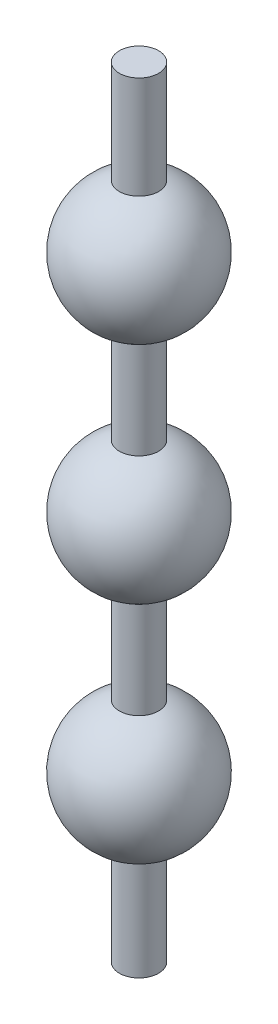
SolidWorks part; units mm, degrees
ref_plane "Front Plane" through (0, 0, 0) normal (0, 0, 1) x (1, 0, 0)
ref_plane "Top Plane" through (0, 0, 0) normal (0, 1, 0) x (1, 0, 0)
ref_plane "Right Plane" through (0, 0, 0) normal (1, 0, 0) x (0, 0, -1)
sketch "Sketch1" plane through (0, 0, 0) normal (0, 1, 0) x (1, 0, 0)
  circle A0 centre (0, 0) radius 1.905
  dimension "D1" = 3.81
extrude "Boss-Extrude1" add sketch "Sketch1" along normal blind 10.16
sketch "Sketch3" plane through (0, 0, 0) normal (0, 0, 1) x (1, 0, 0)
  line L0 (0, 9.652) -> (0, 22.352)
  line L2 (1.905, 10.16) -> (-1.905, 10.16) construction
  arc A0 (0, 9.652) -> (0, 22.352) centre (0, 16.002) ccw
  point P2 (0, 9.3041)
  dimension "D1" = 12.7
  dimension "D2" = 0.508
revolve "Revolve1" add sketch "Sketch3" angle 360 about L0
ref_plane "Plane1" through (0, 21.844, 0) normal (0, -1, 0) x (-1, 0, 0)
sketch "Sketch4" plane through (0, 21.844, 0) normal (0, -1, 0) x (-1, 0, 0)
  circle A0 centre (0, 0) radius 1.905
  dimension "D1" = 3.81
extrude "Boss-Extrude2" add sketch "Sketch4" against normal blind 10.16 contours A0
sketch "Sketch6" plane through (0, 0, 0) normal (0, 0, 1) x (1, 0, 0)
  line L0 (0, 31.496) -> (0, 44.196)
  line L1 (1.905, 32.004) -> (-1.905, 32.004) construction
  arc A0 (0, 31.496) -> (0, 44.196) centre (0, 37.846) ccw
  dimension "D1" = 12.7
  dimension "D2" = 0.508
revolve "Revolve2" add sketch "Sketch6" angle 360 about L0
ref_plane "Plane2" through (0, 43.688, 0) normal (0, -1, 0) x (-1, 0, 0)
sketch "Sketch7" plane through (0, 43.688, 0) normal (0, -1, 0) x (-1, 0, 0)
  circle A0 centre (0, 0) radius 1.905
  dimension "D1" = 3.81
extrude "Boss-Extrude3" add sketch "Sketch7" against normal blind 10.16
sketch "Sketch8" plane through (0, 0, 0) normal (1, 0, 0) x (0, 0, -1)
  line L0 (0, 53.34) -> (0, 66.04)
  line L1 (1.905, 53.848) -> (-1.905, 53.848) construction
  arc A0 (0, 53.34) -> (0, 66.04) centre (0, 59.69) ccw
  dimension "D1" = 12.7
  dimension "D2" = 0.508
revolve "Revolve3" add sketch "Sketch8" angle 360 about L0
ref_plane "Plane3" through (0, 65.532, 0) normal (0, -1, 0) x (-1, 0, 0)
sketch "Sketch9" plane through (0, 65.532, 0) normal (0, -1, 0) x (-1, 0, 0)
  circle A0 centre (0, 0) radius 1.905
  dimension "D1" = 3.81
extrude "Boss-Extrude4" add sketch "Sketch9" against normal blind 10.16
equation "\"Connector Diameter\"= .15"
equation "\"Ball Diameter\"= .5"
equation "\"Connector Length\"= .4"
equation "\"D1@Sketch1\"=\"Connector Diameter\""
equation "\"D1@Boss-Extrude1\"=\"Connector Length\""
equation "\"D1@Sketch3\"=\"Ball Diameter\""
equation "\"Ball Overlap\"= 0.02"
equation "\"D1@Sketch4\"=\"Connector Diameter\""
equation "\"D1@Boss-Extrude2\"=\"Connector Length\""
equation "\"D1@Sketch6\"=\"Ball Diameter\""
equation "\"D2@Sketch6\"=\"Ball Overlap\""
equation "\"D1@Sketch7\"=\"Connector Diameter\""
equation "\"D1@Boss-Extrude3\"=\"Connector Length\""
equation "\"D1@Sketch8\"=\"Ball Diameter\""
equation "\"D2@Sketch8\"=\"Ball Overlap\""
equation "\"D1@Sketch9\"=\"Connector Diameter\""
equation "\"D1@Boss-Extrude4\"=\"Connector Length\""
